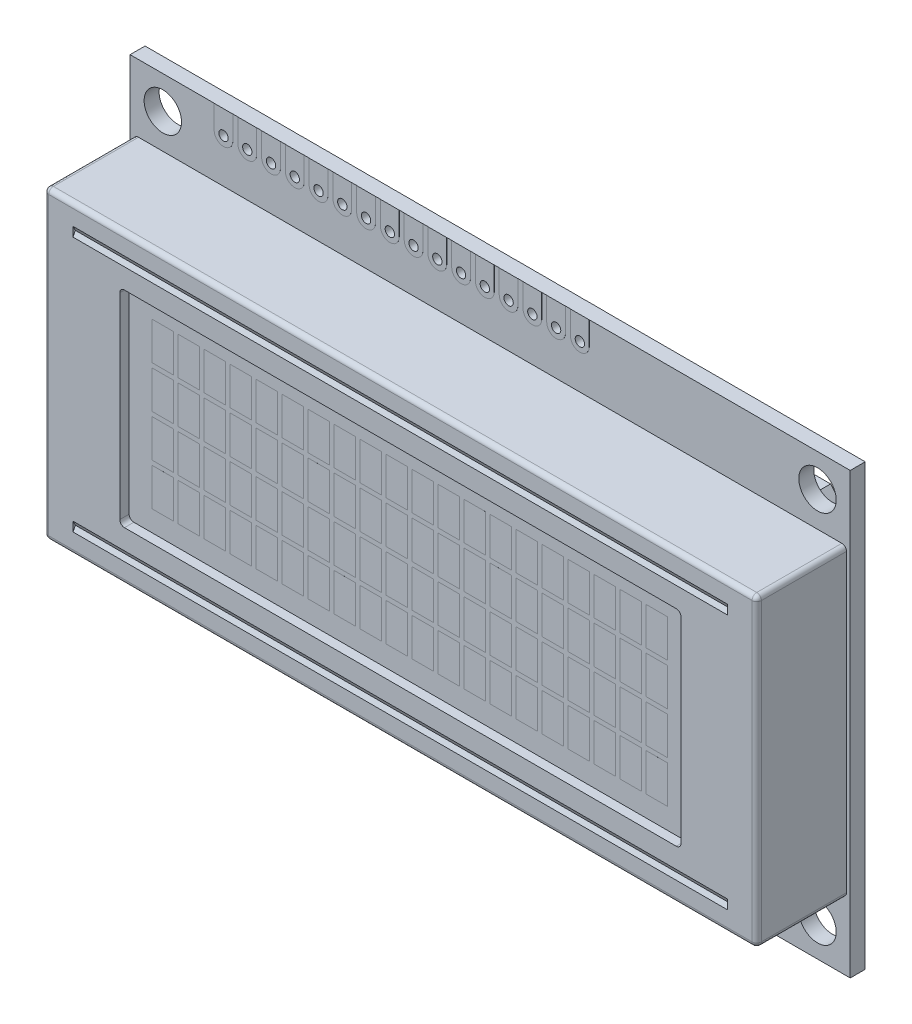
SolidWorks part; units mm, degrees
ref_plane "Plan de face" through (0, 0, 0) normal (0, 0, 1) x (1, 0, 0)
ref_plane "Plan de dessus" through (0, 0, 0) normal (0, 1, 0) x (1, 0, 0)
ref_plane "Plan de droite" through (0, 0, 0) normal (1, 0, 0) x (0, 0, -1)
sketch "Esquisse1" plane through (0, 0, 0) normal (0, 0, 1) x (1, 0, 0)
  line L0 (0, 23.5) -> (0, -23.5) construction
  line L1 (-38.5, 23.5) -> (38.5, 23.5)
  line L2 (-38.5, 23.5) -> (-38.5, -23.5)
  line L3 (-38.5, -23.5) -> (38.5, -23.5)
  line L4 (38.5, 23.5) -> (38.5, -23.5)
  line L5 (-38.5, 23.5) -> (38.5, -23.5) construction
  line L6 (-38.5, -23.5) -> (38.5, 23.5) construction
  line L7 (-38.5, 0) -> (38.5, 0) construction
  line L8 (-28.5, 21) -> (-25.96, 21) construction
  circle A0 centre (-35, 20) radius 2
  circle A1 centre (35, 20) radius 2
  circle A2 centre (-35, -20) radius 2
  circle A3 centre (35, -20) radius 2
  circle A4 centre (-28.5, 21) radius 0.5
  circle A5 centre (-25.96, 21) radius 0.5
  circle A6 centre (-23.42, 21) radius 0.5
  circle A7 centre (-20.88, 21) radius 0.5
  circle A8 centre (-18.34, 21) radius 0.5
  circle A9 centre (-15.8, 21) radius 0.5
  circle A10 centre (-13.26, 21) radius 0.5
  circle A11 centre (-10.72, 21) radius 0.5
  circle A12 centre (-8.18, 21) radius 0.5
  circle A13 centre (-5.64, 21) radius 0.5
  circle A14 centre (-3.1, 21) radius 0.5
  circle A15 centre (-0.56, 21) radius 0.5
  circle A16 centre (1.98, 21) radius 0.5
  circle A17 centre (4.52, 21) radius 0.5
  circle A18 centre (7.06, 21) radius 0.5
  circle A19 centre (9.6, 21) radius 0.5
  point P0 (0, 0)
  dimension "D3" = 4
  dimension "D6" = 10
  dimension "D7" = 1
  dimension "D1" = 77
  dimension "D2" = 47
  dimension "D4" = 40
  dimension "D5" = 70
  dimension "D8" = 2.5
  dimension "D10" = 2.54
  dimension "D9" = 16
extrude "PCB" add sketch "Esquisse1" along normal blind 1.6
ref_plane "Plan mi-PCB" through (0, 0, 0.8) normal (0, 0, 1) x (1, 0, 0)
sketch "Esquisse6" plane through (0, 0, 1.6) normal (0, 0, 1) x (1, 0, 0)
  line L0 (-29.5, 21) -> (-29.5, 23.5)
  line L1 (38.5, 23.5) -> (-38.5, 23.5) construction
  line L2 (-29.5, 23.5) -> (-27.5, 23.5)
  line L3 (-27.5, 23.5) -> (-27.5, 21)
  line L4 (-24.96, 23.5) -> (-24.96, 21)
  line L5 (-26.96, 21) -> (-26.96, 23.5)
  line L6 (-26.96, 23.5) -> (-24.96, 23.5)
  line L7 (-22.42, 23.5) -> (-22.42, 21)
  line L8 (-24.42, 21) -> (-24.42, 23.5)
  line L9 (-24.42, 23.5) -> (-22.42, 23.5)
  line L10 (-19.88, 23.5) -> (-19.88, 21)
  line L11 (-21.88, 21) -> (-21.88, 23.5)
  line L12 (-21.88, 23.5) -> (-19.88, 23.5)
  line L13 (-17.34, 23.5) -> (-17.34, 21)
  line L14 (-19.34, 21) -> (-19.34, 23.5)
  line L15 (-19.34, 23.5) -> (-17.34, 23.5)
  line L16 (-14.8, 23.5) -> (-14.8, 21)
  line L17 (-16.8, 21) -> (-16.8, 23.5)
  line L18 (-16.8, 23.5) -> (-14.8, 23.5)
  line L19 (-12.26, 23.5) -> (-12.26, 21)
  line L20 (-14.26, 21) -> (-14.26, 23.5)
  line L21 (-14.26, 23.5) -> (-12.26, 23.5)
  line L22 (-9.72, 23.5) -> (-9.72, 21)
  line L23 (-11.72, 21) -> (-11.72, 23.5)
  line L24 (-11.72, 23.5) -> (-9.72, 23.5)
  line L25 (-7.18, 23.5) -> (-7.18, 21)
  line L26 (-9.18, 21) -> (-9.18, 23.5)
  line L27 (-9.18, 23.5) -> (-7.18, 23.5)
  line L28 (-4.64, 23.5) -> (-4.64, 21)
  line L29 (-6.64, 21) -> (-6.64, 23.5)
  line L30 (-6.64, 23.5) -> (-4.64, 23.5)
  line L31 (-2.1, 23.5) -> (-2.1, 21)
  line L32 (-4.1, 21) -> (-4.1, 23.5)
  line L33 (-4.1, 23.5) -> (-2.1, 23.5)
  line L34 (0.44, 23.5) -> (0.44, 21)
  line L35 (-1.56, 21) -> (-1.56, 23.5)
  line L36 (-1.56, 23.5) -> (0.44, 23.5)
  line L37 (2.98, 23.5) -> (2.98, 21)
  line L38 (0.98, 21) -> (0.98, 23.5)
  line L39 (0.98, 23.5) -> (2.98, 23.5)
  line L40 (5.52, 23.5) -> (5.52, 21)
  line L41 (3.52, 21) -> (3.52, 23.5)
  line L42 (3.52, 23.5) -> (5.52, 23.5)
  line L43 (8.06, 23.5) -> (8.06, 21)
  line L44 (6.06, 21) -> (6.06, 23.5)
  line L45 (6.06, 23.5) -> (8.06, 23.5)
  line L46 (10.6, 23.5) -> (10.6, 21)
  line L47 (8.6, 21) -> (8.6, 23.5)
  line L48 (8.6, 23.5) -> (10.6, 23.5)
  line L49 (-27.5, 23.5) -> (-24.96, 23.5) construction
  arc A0 (-29.5, 21) -> (-27.5, 21) centre (-28.5, 21) ccw
  circle A1 centre (-28.5, 21) radius 0.5 construction
  circle A2 centre (-28.5, 21) radius 0.5
  arc A3 (-26.96, 21) -> (-24.96, 21) centre (-25.96, 21) ccw
  circle A4 centre (-25.96, 21) radius 0.5
  arc A5 (-24.42, 21) -> (-22.42, 21) centre (-23.42, 21) ccw
  circle A6 centre (-23.42, 21) radius 0.5
  arc A7 (-21.88, 21) -> (-19.88, 21) centre (-20.88, 21) ccw
  circle A8 centre (-20.88, 21) radius 0.5
  arc A9 (-19.34, 21) -> (-17.34, 21) centre (-18.34, 21) ccw
  circle A10 centre (-18.34, 21) radius 0.5
  arc A11 (-16.8, 21) -> (-14.8, 21) centre (-15.8, 21) ccw
  circle A12 centre (-15.8, 21) radius 0.5
  arc A13 (-14.26, 21) -> (-12.26, 21) centre (-13.26, 21) ccw
  circle A14 centre (-13.26, 21) radius 0.5
  arc A15 (-11.72, 21) -> (-9.72, 21) centre (-10.72, 21) ccw
  circle A16 centre (-10.72, 21) radius 0.5
  arc A17 (-9.18, 21) -> (-7.18, 21) centre (-8.18, 21) ccw
  circle A18 centre (-8.18, 21) radius 0.5
  arc A19 (-6.64, 21) -> (-4.64, 21) centre (-5.64, 21) ccw
  circle A20 centre (-5.64, 21) radius 0.5
  arc A21 (-4.1, 21) -> (-2.1, 21) centre (-3.1, 21) ccw
  circle A22 centre (-3.1, 21) radius 0.5
  arc A23 (-1.56, 21) -> (0.44, 21) centre (-0.56, 21) ccw
  circle A24 centre (-0.56, 21) radius 0.5
  arc A25 (0.98, 21) -> (2.98, 21) centre (1.98, 21) ccw
  circle A26 centre (1.98, 21) radius 0.5
  arc A27 (3.52, 21) -> (5.52, 21) centre (4.52, 21) ccw
  circle A28 centre (4.52, 21) radius 0.5
  arc A29 (6.06, 21) -> (8.06, 21) centre (7.06, 21) ccw
  circle A30 centre (7.06, 21) radius 0.5
  arc A31 (8.6, 21) -> (10.6, 21) centre (9.6, 21) ccw
  circle A32 centre (9.6, 21) radius 0.5
  dimension "D1" = 2
  dimension "D3" = 2.54
  dimension "D2" = 16
extrude "Pads" add sketch "Esquisse6" along normal blind 0.01
mirror "Symétrie1" about plane through (0, 0, 0.8) normal (0, 0, 1) of "Pads"
sketch "Esquisse2" plane through (0, 0, 1.6) normal (0, 0, 1) x (1, 0, 0)
  line L0 (38.5, 23.5) -> (10.6, 23.5) construction
  line L1 (-38.1, 16.3) -> (38.1, 16.3)
  line L2 (-38.1, 16.3) -> (-38.1, -16.3)
  line L3 (-38.1, -16.3) -> (38.1, -16.3)
  line L4 (38.1, 16.3) -> (38.1, -16.3)
  line L5 (-38.1, 16.3) -> (38.1, -16.3) construction
  line L6 (-38.1, -16.3) -> (38.1, 16.3) construction
  line L7 (38.5, -23.5) -> (38.5, 23.5) construction
  point P0 (0, 0)
  dimension "D1" = 76.2
  dimension "D2" = 32.6
  dimension "D3" = 7.2
  dimension "D4" = 0.4
extrude "capot ecran" add sketch "Esquisse2" along normal blind 9.6
fillet "Congé capot" radius 0.5 8 edges at (0, -16.3, 11.2) (-38.1, 0, 11.2) (0, 16.3, 11.2) (38.1, 0, 11.2) (-38.1, -16.3, 6.4) (-38.1, 16.3, 6.4) (38.1, -16.3, 6.4) (38.1, 16.3, 6.4)
sketch "Esquisse3" plane through (0, 0, 11.2) normal (0, 0, 1) x (1, 0, 0)
  line L1 (-29.5, 11) -> (29.5, 11)
  line L2 (-30, 10.5) -> (-30, -10.5)
  line L3 (-29.5, -11) -> (29.5, -11)
  line L4 (30, 10.5) -> (30, -10.5)
  line L5 (-30, 11) -> (30, -11) construction
  line L6 (-30, -11) -> (30, 11) construction
  line L7 (38.5, -23.5) -> (38.5, 23.5) construction
  line L8 (38.5, 23.5) -> (10.6, 23.5) construction
  arc A0 (30, -10.5) -> (29.5, -11) centre (29.5, -10.5) cw
  arc A1 (-29.5, -11) -> (-30, -10.5) centre (-29.5, -10.5) cw
  arc A2 (-30, 10.5) -> (-29.5, 11) centre (-29.5, 10.5) cw
  arc A3 (29.5, 11) -> (30, 10.5) centre (29.5, 10.5) cw
  point P0 (0, 0)
  dimension "D3" = 0.5
  dimension "D1" = 60
  dimension "D2" = 22
  dimension "D4" = 8.5
  dimension "D5" = 12.5
extrude "ecran" cut sketch "Esquisse3" against normal blind 1
sketch "Esquisse4" plane through (0, 0, 10.2) normal (0, 0, 1) x (1, 0, 0)
  line L0 (-24.78, 4.75) -> (-22.48, 4.75)
  line L1 (-27.56, 8.78) -> (-25.26, 8.78)
  line L2 (-27.56, 8.78) -> (-27.56, 4.75)
  line L3 (-27.56, 4.75) -> (-25.26, 4.75)
  line L4 (-25.26, 8.78) -> (-25.26, 4.75)
  line L5 (-22.48, 8.78) -> (-22.48, 4.75)
  line L6 (-24.78, 8.78) -> (-22.48, 8.78)
  line L7 (-24.78, 8.78) -> (-24.78, 4.75)
  line L8 (-22, 4.75) -> (-19.7, 4.75)
  line L9 (-19.7, 8.78) -> (-19.7, 4.75)
  line L10 (-22, 8.78) -> (-19.7, 8.78)
  line L11 (-22, 8.78) -> (-22, 4.75)
  line L12 (-19.22, 4.75) -> (-16.92, 4.75)
  line L13 (-16.92, 8.78) -> (-16.92, 4.75)
  line L14 (-19.22, 8.78) -> (-16.92, 8.78)
  line L15 (-19.22, 8.78) -> (-19.22, 4.75)
  line L16 (-16.44, 4.75) -> (-14.14, 4.75)
  line L17 (-14.14, 8.78) -> (-14.14, 4.75)
  line L18 (-16.44, 8.78) -> (-14.14, 8.78)
  line L19 (-16.44, 8.78) -> (-16.44, 4.75)
  line L20 (-13.66, 4.75) -> (-11.36, 4.75)
  line L21 (-11.36, 8.78) -> (-11.36, 4.75)
  line L22 (-13.66, 8.78) -> (-11.36, 8.78)
  line L23 (-13.66, 8.78) -> (-13.66, 4.75)
  line L24 (-10.88, 4.75) -> (-8.58, 4.75)
  line L25 (-8.58, 8.78) -> (-8.58, 4.75)
  line L26 (-10.88, 8.78) -> (-8.58, 8.78)
  line L27 (-10.88, 8.78) -> (-10.88, 4.75)
  line L28 (-8.1, 4.75) -> (-5.8, 4.75)
  line L29 (-5.8, 8.78) -> (-5.8, 4.75)
  line L30 (-8.1, 8.78) -> (-5.8, 8.78)
  line L31 (-8.1, 8.78) -> (-8.1, 4.75)
  line L32 (-5.32, 4.75) -> (-3.02, 4.75)
  line L33 (-3.02, 8.78) -> (-3.02, 4.75)
  line L34 (-5.32, 8.78) -> (-3.02, 8.78)
  line L35 (-5.32, 8.78) -> (-5.32, 4.75)
  line L36 (-2.54, 4.75) -> (-0.24, 4.75)
  line L37 (-0.24, 8.78) -> (-0.24, 4.75)
  line L38 (-2.54, 8.78) -> (-0.24, 8.78)
  line L39 (-2.54, 8.78) -> (-2.54, 4.75)
  line L40 (0.24, 4.75) -> (2.54, 4.75)
  line L41 (2.54, 8.78) -> (2.54, 4.75)
  line L42 (0.24, 8.78) -> (2.54, 8.78)
  line L43 (0.24, 8.78) -> (0.24, 4.75)
  line L44 (3.02, 4.75) -> (5.32, 4.75)
  line L45 (5.32, 8.78) -> (5.32, 4.75)
  line L46 (3.02, 8.78) -> (5.32, 8.78)
  line L47 (3.02, 8.78) -> (3.02, 4.75)
  line L48 (5.8, 4.75) -> (8.1, 4.75)
  line L49 (8.1, 8.78) -> (8.1, 4.75)
  line L50 (5.8, 8.78) -> (8.1, 8.78)
  line L51 (5.8, 8.78) -> (5.8, 4.75)
  line L52 (8.58, 4.75) -> (10.88, 4.75)
  line L53 (10.88, 8.78) -> (10.88, 4.75)
  line L54 (8.58, 8.78) -> (10.88, 8.78)
  line L55 (8.58, 8.78) -> (8.58, 4.75)
  line L56 (11.36, 4.75) -> (13.66, 4.75)
  line L57 (13.66, 8.78) -> (13.66, 4.75)
  line L58 (11.36, 8.78) -> (13.66, 8.78)
  line L59 (11.36, 8.78) -> (11.36, 4.75)
  line L60 (14.14, 4.75) -> (16.44, 4.75)
  line L61 (16.44, 8.78) -> (16.44, 4.75)
  line L62 (14.14, 8.78) -> (16.44, 8.78)
  line L63 (14.14, 8.78) -> (14.14, 4.75)
  line L64 (16.92, 4.75) -> (19.22, 4.75)
  line L65 (19.22, 8.78) -> (19.22, 4.75)
  line L66 (16.92, 8.78) -> (19.22, 8.78)
  line L67 (16.92, 8.78) -> (16.92, 4.75)
  line L68 (19.7, 4.75) -> (22, 4.75)
  line L69 (22, 8.78) -> (22, 4.75)
  line L70 (19.7, 8.78) -> (22, 8.78)
  line L71 (19.7, 8.78) -> (19.7, 4.75)
  line L72 (22.48, 4.75) -> (24.78, 4.75)
  line L73 (24.78, 8.78) -> (24.78, 4.75)
  line L74 (22.48, 8.78) -> (24.78, 8.78)
  line L75 (22.48, 8.78) -> (22.48, 4.75)
  line L76 (25.26, 4.75) -> (27.56, 4.75)
  line L77 (27.56, 8.78) -> (27.56, 4.75)
  line L78 (25.26, 8.78) -> (27.56, 8.78)
  line L79 (25.26, 8.78) -> (25.26, 4.75)
  line L80 (-24.78, 0.24) -> (-22.48, 0.24)
  line L81 (-22.48, 4.27) -> (-22.48, 0.24)
  line L82 (-24.78, 4.27) -> (-22.48, 4.27)
  line L83 (-24.78, 4.27) -> (-24.78, 0.24)
  line L84 (-22, 0.24) -> (-19.7, 0.24)
  line L85 (-19.7, 4.27) -> (-19.7, 0.24)
  line L86 (-22, 4.27) -> (-19.7, 4.27)
  line L87 (-22, 4.27) -> (-22, 0.24)
  line L88 (-19.22, 0.24) -> (-16.92, 0.24)
  line L89 (-16.92, 4.27) -> (-16.92, 0.24)
  line L90 (-19.22, 4.27) -> (-16.92, 4.27)
  line L91 (-19.22, 4.27) -> (-19.22, 0.24)
  line L92 (-16.44, 0.24) -> (-14.14, 0.24)
  line L93 (-14.14, 4.27) -> (-14.14, 0.24)
  line L94 (-16.44, 4.27) -> (-14.14, 4.27)
  line L95 (-16.44, 4.27) -> (-16.44, 0.24)
  line L96 (-13.66, 0.24) -> (-11.36, 0.24)
  line L97 (-11.36, 4.27) -> (-11.36, 0.24)
  line L98 (-13.66, 4.27) -> (-11.36, 4.27)
  line L99 (-13.66, 4.27) -> (-13.66, 0.24)
  line L100 (-10.88, 0.24) -> (-8.58, 0.24)
  line L101 (-8.58, 4.27) -> (-8.58, 0.24)
  line L102 (-10.88, 4.27) -> (-8.58, 4.27)
  line L103 (-10.88, 4.27) -> (-10.88, 0.24)
  line L104 (-8.1, 0.24) -> (-5.8, 0.24)
  line L105 (-5.8, 4.27) -> (-5.8, 0.24)
  line L106 (-8.1, 4.27) -> (-5.8, 4.27)
  line L107 (-8.1, 4.27) -> (-8.1, 0.24)
  line L108 (-5.32, 0.24) -> (-3.02, 0.24)
  line L109 (-3.02, 4.27) -> (-3.02, 0.24)
  line L110 (-5.32, 4.27) -> (-3.02, 4.27)
  line L111 (-5.32, 4.27) -> (-5.32, 0.24)
  line L112 (-2.54, 0.24) -> (-0.24, 0.24)
  line L113 (-0.24, 4.27) -> (-0.24, 0.24)
  line L114 (-2.54, 4.27) -> (-0.24, 4.27)
  line L115 (-2.54, 4.27) -> (-2.54, 0.24)
  line L116 (0.24, 0.24) -> (2.54, 0.24)
  line L117 (2.54, 4.27) -> (2.54, 0.24)
  line L118 (0.24, 4.27) -> (2.54, 4.27)
  line L119 (0.24, 4.27) -> (0.24, 0.24)
  line L120 (3.02, 0.24) -> (5.32, 0.24)
  line L121 (5.32, 4.27) -> (5.32, 0.24)
  line L122 (3.02, 4.27) -> (5.32, 4.27)
  line L123 (3.02, 4.27) -> (3.02, 0.24)
  line L124 (5.8, 0.24) -> (8.1, 0.24)
  line L125 (8.1, 4.27) -> (8.1, 0.24)
  line L126 (5.8, 4.27) -> (8.1, 4.27)
  line L127 (5.8, 4.27) -> (5.8, 0.24)
  line L128 (8.58, 0.24) -> (10.88, 0.24)
  line L129 (10.88, 4.27) -> (10.88, 0.24)
  line L130 (8.58, 4.27) -> (10.88, 4.27)
  line L131 (8.58, 4.27) -> (8.58, 0.24)
  line L132 (11.36, 0.24) -> (13.66, 0.24)
  line L133 (13.66, 4.27) -> (13.66, 0.24)
  line L134 (11.36, 4.27) -> (13.66, 4.27)
  line L135 (11.36, 4.27) -> (11.36, 0.24)
  line L136 (14.14, 0.24) -> (16.44, 0.24)
  line L137 (16.44, 4.27) -> (16.44, 0.24)
  line L138 (14.14, 4.27) -> (16.44, 4.27)
  line L139 (14.14, 4.27) -> (14.14, 0.24)
  line L140 (16.92, 0.24) -> (19.22, 0.24)
  line L141 (19.22, 4.27) -> (19.22, 0.24)
  line L142 (16.92, 4.27) -> (19.22, 4.27)
  line L143 (16.92, 4.27) -> (16.92, 0.24)
  line L144 (19.7, 0.24) -> (22, 0.24)
  line L145 (22, 4.27) -> (22, 0.24)
  line L146 (19.7, 4.27) -> (22, 4.27)
  line L147 (19.7, 4.27) -> (19.7, 0.24)
  line L148 (22.48, 0.24) -> (24.78, 0.24)
  line L149 (24.78, 4.27) -> (24.78, 0.24)
  line L150 (22.48, 4.27) -> (24.78, 4.27)
  line L151 (22.48, 4.27) -> (22.48, 0.24)
  line L152 (25.26, 0.24) -> (27.56, 0.24)
  line L153 (27.56, 4.27) -> (27.56, 0.24)
  line L154 (25.26, 4.27) -> (27.56, 4.27)
  line L155 (25.26, 4.27) -> (25.26, 0.24)
  line L156 (-24.78, -4.27) -> (-22.48, -4.27)
  line L157 (-22.48, -0.24) -> (-22.48, -4.27)
  line L158 (-24.78, -0.24) -> (-22.48, -0.24)
  line L159 (-24.78, -0.24) -> (-24.78, -4.27)
  line L160 (-22, -4.27) -> (-19.7, -4.27)
  line L161 (-19.7, -0.24) -> (-19.7, -4.27)
  line L162 (-22, -0.24) -> (-19.7, -0.24)
  line L163 (-22, -0.24) -> (-22, -4.27)
  line L164 (-19.22, -4.27) -> (-16.92, -4.27)
  line L165 (-16.92, -0.24) -> (-16.92, -4.27)
  line L166 (-19.22, -0.24) -> (-16.92, -0.24)
  line L167 (-19.22, -0.24) -> (-19.22, -4.27)
  line L168 (-16.44, -4.27) -> (-14.14, -4.27)
  line L169 (-14.14, -0.24) -> (-14.14, -4.27)
  line L170 (-16.44, -0.24) -> (-14.14, -0.24)
  line L171 (-16.44, -0.24) -> (-16.44, -4.27)
  line L172 (-13.66, -4.27) -> (-11.36, -4.27)
  line L173 (-11.36, -0.24) -> (-11.36, -4.27)
  line L174 (-13.66, -0.24) -> (-11.36, -0.24)
  line L175 (-13.66, -0.24) -> (-13.66, -4.27)
  line L176 (-10.88, -4.27) -> (-8.58, -4.27)
  line L177 (-8.58, -0.24) -> (-8.58, -4.27)
  line L178 (-10.88, -0.24) -> (-8.58, -0.24)
  line L179 (-10.88, -0.24) -> (-10.88, -4.27)
  line L180 (-8.1, -4.27) -> (-5.8, -4.27)
  line L181 (-5.8, -0.24) -> (-5.8, -4.27)
  line L182 (-8.1, -0.24) -> (-5.8, -0.24)
  line L183 (-8.1, -0.24) -> (-8.1, -4.27)
  line L184 (-5.32, -4.27) -> (-3.02, -4.27)
  line L185 (-3.02, -0.24) -> (-3.02, -4.27)
  line L186 (-5.32, -0.24) -> (-3.02, -0.24)
  line L187 (-5.32, -0.24) -> (-5.32, -4.27)
  line L188 (-2.54, -4.27) -> (-0.24, -4.27)
  line L189 (-0.24, -0.24) -> (-0.24, -4.27)
  line L190 (-2.54, -0.24) -> (-0.24, -0.24)
  line L191 (-2.54, -0.24) -> (-2.54, -4.27)
  line L192 (0.24, -4.27) -> (2.54, -4.27)
  line L193 (2.54, -0.24) -> (2.54, -4.27)
  line L194 (0.24, -0.24) -> (2.54, -0.24)
  line L195 (0.24, -0.24) -> (0.24, -4.27)
  line L196 (3.02, -4.27) -> (5.32, -4.27)
  line L197 (5.32, -0.24) -> (5.32, -4.27)
  line L198 (3.02, -0.24) -> (5.32, -0.24)
  line L199 (3.02, -0.24) -> (3.02, -4.27)
  line L200 (5.8, -4.27) -> (8.1, -4.27)
  line L201 (8.1, -0.24) -> (8.1, -4.27)
  line L202 (5.8, -0.24) -> (8.1, -0.24)
  line L203 (5.8, -0.24) -> (5.8, -4.27)
  line L204 (8.58, -4.27) -> (10.88, -4.27)
  line L205 (10.88, -0.24) -> (10.88, -4.27)
  line L206 (8.58, -0.24) -> (10.88, -0.24)
  line L207 (8.58, -0.24) -> (8.58, -4.27)
  line L208 (11.36, -4.27) -> (13.66, -4.27)
  line L209 (13.66, -0.24) -> (13.66, -4.27)
  line L210 (11.36, -0.24) -> (13.66, -0.24)
  line L211 (11.36, -0.24) -> (11.36, -4.27)
  line L212 (14.14, -4.27) -> (16.44, -4.27)
  line L213 (16.44, -0.24) -> (16.44, -4.27)
  line L214 (14.14, -0.24) -> (16.44, -0.24)
  line L215 (14.14, -0.24) -> (14.14, -4.27)
  line L216 (16.92, -4.27) -> (19.22, -4.27)
  line L217 (19.22, -0.24) -> (19.22, -4.27)
  line L218 (16.92, -0.24) -> (19.22, -0.24)
  line L219 (16.92, -0.24) -> (16.92, -4.27)
  line L220 (19.7, -4.27) -> (22, -4.27)
  line L221 (22, -0.24) -> (22, -4.27)
  line L222 (19.7, -0.24) -> (22, -0.24)
  line L223 (19.7, -0.24) -> (19.7, -4.27)
  line L224 (22.48, -4.27) -> (24.78, -4.27)
  line L225 (24.78, -0.24) -> (24.78, -4.27)
  line L226 (22.48, -0.24) -> (24.78, -0.24)
  line L227 (22.48, -0.24) -> (22.48, -4.27)
  line L228 (25.26, -4.27) -> (27.56, -4.27)
  line L229 (27.56, -0.24) -> (27.56, -4.27)
  line L230 (25.26, -0.24) -> (27.56, -0.24)
  line L231 (25.26, -0.24) -> (25.26, -4.27)
  line L232 (-24.78, -8.78) -> (-22.48, -8.78)
  line L233 (-22.48, -4.75) -> (-22.48, -8.78)
  line L234 (-24.78, -4.75) -> (-22.48, -4.75)
  line L235 (-24.78, -4.75) -> (-24.78, -8.78)
  line L236 (-22, -8.78) -> (-19.7, -8.78)
  line L237 (-19.7, -4.75) -> (-19.7, -8.78)
  line L238 (-22, -4.75) -> (-19.7, -4.75)
  line L239 (-22, -4.75) -> (-22, -8.78)
  line L240 (-19.22, -8.78) -> (-16.92, -8.78)
  line L241 (-16.92, -4.75) -> (-16.92, -8.78)
  line L242 (-19.22, -4.75) -> (-16.92, -4.75)
  line L243 (-19.22, -4.75) -> (-19.22, -8.78)
  line L244 (-16.44, -8.78) -> (-14.14, -8.78)
  line L245 (-14.14, -4.75) -> (-14.14, -8.78)
  line L246 (-16.44, -4.75) -> (-14.14, -4.75)
  line L247 (-16.44, -4.75) -> (-16.44, -8.78)
  line L248 (-13.66, -8.78) -> (-11.36, -8.78)
  line L249 (-11.36, -4.75) -> (-11.36, -8.78)
  line L250 (-13.66, -4.75) -> (-11.36, -4.75)
  line L251 (-13.66, -4.75) -> (-13.66, -8.78)
  line L252 (-10.88, -8.78) -> (-8.58, -8.78)
  line L253 (-8.58, -4.75) -> (-8.58, -8.78)
  line L254 (-10.88, -4.75) -> (-8.58, -4.75)
  line L255 (-10.88, -4.75) -> (-10.88, -8.78)
  line L256 (-8.1, -8.78) -> (-5.8, -8.78)
  line L257 (-5.8, -4.75) -> (-5.8, -8.78)
  line L258 (-8.1, -4.75) -> (-5.8, -4.75)
  line L259 (-8.1, -4.75) -> (-8.1, -8.78)
  line L260 (-5.32, -8.78) -> (-3.02, -8.78)
  line L261 (-3.02, -4.75) -> (-3.02, -8.78)
  line L262 (-5.32, -4.75) -> (-3.02, -4.75)
  line L263 (-5.32, -4.75) -> (-5.32, -8.78)
  line L264 (-2.54, -8.78) -> (-0.24, -8.78)
  line L265 (-0.24, -4.75) -> (-0.24, -8.78)
  line L266 (-2.54, -4.75) -> (-0.24, -4.75)
  line L267 (-2.54, -4.75) -> (-2.54, -8.78)
  line L268 (0.24, -8.78) -> (2.54, -8.78)
  line L269 (2.54, -4.75) -> (2.54, -8.78)
  line L270 (0.24, -4.75) -> (2.54, -4.75)
  line L271 (0.24, -4.75) -> (0.24, -8.78)
  line L272 (3.02, -8.78) -> (5.32, -8.78)
  line L273 (5.32, -4.75) -> (5.32, -8.78)
  line L274 (3.02, -4.75) -> (5.32, -4.75)
  line L275 (3.02, -4.75) -> (3.02, -8.78)
  line L276 (5.8, -8.78) -> (8.1, -8.78)
  line L277 (8.1, -4.75) -> (8.1, -8.78)
  line L278 (5.8, -4.75) -> (8.1, -4.75)
  line L279 (5.8, -4.75) -> (5.8, -8.78)
  line L280 (8.58, -8.78) -> (10.88, -8.78)
  line L281 (10.88, -4.75) -> (10.88, -8.78)
  line L282 (8.58, -4.75) -> (10.88, -4.75)
  line L283 (8.58, -4.75) -> (8.58, -8.78)
  line L284 (11.36, -8.78) -> (13.66, -8.78)
  line L285 (13.66, -4.75) -> (13.66, -8.78)
  line L286 (11.36, -4.75) -> (13.66, -4.75)
  line L287 (11.36, -4.75) -> (11.36, -8.78)
  line L288 (14.14, -8.78) -> (16.44, -8.78)
  line L289 (16.44, -4.75) -> (16.44, -8.78)
  line L290 (14.14, -4.75) -> (16.44, -4.75)
  line L291 (14.14, -4.75) -> (14.14, -8.78)
  line L292 (16.92, -8.78) -> (19.22, -8.78)
  line L293 (19.22, -4.75) -> (19.22, -8.78)
  line L294 (16.92, -4.75) -> (19.22, -4.75)
  line L295 (16.92, -4.75) -> (16.92, -8.78)
  line L296 (19.7, -8.78) -> (22, -8.78)
  line L297 (22, -4.75) -> (22, -8.78)
  line L298 (19.7, -4.75) -> (22, -4.75)
  line L299 (19.7, -4.75) -> (19.7, -8.78)
  line L300 (22.48, -8.78) -> (24.78, -8.78)
  line L301 (24.78, -4.75) -> (24.78, -8.78)
  line L302 (22.48, -4.75) -> (24.78, -4.75)
  line L303 (22.48, -4.75) -> (22.48, -8.78)
  line L304 (25.26, -8.78) -> (27.56, -8.78)
  line L305 (27.56, -4.75) -> (27.56, -8.78)
  line L306 (25.26, -4.75) -> (27.56, -4.75)
  line L307 (25.26, -4.75) -> (25.26, -8.78)
  line L308 (-27.56, 0.24) -> (-25.26, 0.24)
  line L309 (-25.26, 4.27) -> (-25.26, 0.24)
  line L310 (-27.56, 4.27) -> (-25.26, 4.27)
  line L311 (-27.56, 4.27) -> (-27.56, 0.24)
  line L312 (-27.56, -4.27) -> (-25.26, -4.27)
  line L313 (-25.26, -0.24) -> (-25.26, -4.27)
  line L314 (-27.56, -0.24) -> (-25.26, -0.24)
  line L315 (-27.56, -0.24) -> (-27.56, -4.27)
  line L316 (-27.56, -8.78) -> (-25.26, -8.78)
  line L317 (-25.26, -4.75) -> (-25.26, -8.78)
  line L318 (-27.56, -4.75) -> (-25.26, -4.75)
  line L319 (-27.56, -4.75) -> (-27.56, -8.78)
  line L320 (-27.56, 4.75) -> (-24.78, 4.75) construction
  line L321 (-27.56, 4.75) -> (-27.56, 0.24) construction
  line L322 (0, 11) -> (0, -11) construction
  line L323 (29.5, 11) -> (-29.5, 11) construction
  line L324 (-29.5, -11) -> (29.5, -11) construction
  line L325 (-0.24, 8.78) -> (0.24, 8.78) construction
  line L326 (-27.56, 0.24) -> (-27.56, -0.24) construction
  line L327 (-30, 0) -> (30, 0) construction
  line L328 (-30, 10.5) -> (-30, -10.5) construction
  line L329 (30, -10.5) -> (30, 10.5) construction
  point P4 (0, 8.78)
  point P336 (-27.56, 0)
  dimension "D1" = 2.3
  dimension "D2" = 4.03
  dimension "D5" = 2.78
  dimension "D6" = 4.51
  dimension "D7" = 55.12
  dimension "D8" = 17.56
  dimension "D3" = 20
  dimension "D4" = 4
extrude "caracteres" add sketch "Esquisse4" along normal blind 0.0001
sketch "Esquisse5" plane through (0, 0, 0) normal (1, 0, 0) x (0, 0, -1)
  line L0 (-11.2, 0) -> (-3.384, 0) construction
  line L1 (-11.2, -15.8) -> (-11.2, 15.8) construction
  line L2 (-11.2, 14.15) -> (-11.2, 13.15)
  line L3 (-11.2, 13.15) -> (-10.95, 13.65)
  line L4 (-10.95, 13.65) -> (-11.2, 14.15)
  line L5 (-11.2, -14.15) -> (-11.2, -13.15)
  line L6 (-10.95, -13.65) -> (-11.2, -14.15)
  line L7 (-11.2, -13.15) -> (-10.95, -13.65)
  point P8 (-11.2, 13.65)
  dimension "D1" = 1
  dimension "D2" = 0.25
  dimension "D3" = 27.3
extrude "lignes capot" cut sketch "Esquisse5" against normal mid plane 70
sketch "Esquisse7" plane through (0, 0, 0) normal (0, 0, -1) x (-1, 0, 0)
  line L0 (0, 17.9709) -> (0, -18.837) construction
  line L1 (-32.635, 0) -> (33.2255, 0) construction
  line L2 (28.5, -16.3) -> (28.5, -15.8)
  line L3 (37.6, -16.3) -> (-37.6, -16.3) construction
  line L4 (28.5, -15.8) -> (31.2688, -15.8)
  line L5 (31.2688, -15.8) -> (32.1191, -14.8)
  line L6 (32.1191, -14.8) -> (32.5, -15.1239)
  line L7 (32.5, -15.1239) -> (31.5, -16.3)
  line L8 (31.5, -16.3) -> (28.5, -16.3)
  line L10 (38.5, 23.5) -> (38.5, -23.5) construction
  line L11 (11.5, -16.3) -> (8.5, -16.3)
  line L12 (8.5, -16.3) -> (8.5, -15.8)
  line L13 (8.5, -15.8) -> (11.2688, -15.8)
  line L14 (11.2688, -15.8) -> (12.1191, -14.8)
  line L15 (12.1191, -14.8) -> (12.5, -15.1239)
  line L16 (12.5, -15.1239) -> (11.5, -16.3)
  line L17 (31.5, -16.3) -> (11.5, -16.3) construction
  line L18 (-28.5, -16.3) -> (-28.5, -15.8)
  line L19 (-31.5, -16.3) -> (-28.5, -16.3)
  line L20 (-32.5, -15.1239) -> (-31.5, -16.3)
  line L21 (-32.1191, -14.8) -> (-32.5, -15.1239)
  line L22 (-31.2688, -15.8) -> (-32.1191, -14.8)
  line L23 (-28.5, -15.8) -> (-31.2688, -15.8)
  line L24 (-8.5, -16.3) -> (-8.5, -15.8)
  line L25 (-11.5, -16.3) -> (-8.5, -16.3)
  line L26 (-12.5, -15.1239) -> (-11.5, -16.3)
  line L27 (-12.1191, -14.8) -> (-12.5, -15.1239)
  line L28 (-11.2688, -15.8) -> (-12.1191, -14.8)
  line L29 (-8.5, -15.8) -> (-11.2688, -15.8)
  line L30 (-28.5, 15.8) -> (-31.2688, 15.8)
  line L31 (-28.5, 16.3) -> (-28.5, 15.8)
  line L32 (-31.5, 16.3) -> (-28.5, 16.3)
  line L33 (-32.5, 15.1239) -> (-31.5, 16.3)
  line L34 (-32.1191, 14.8) -> (-32.5, 15.1239)
  line L35 (-31.2688, 15.8) -> (-32.1191, 14.8)
  line L36 (-8.5, 15.8) -> (-11.2688, 15.8)
  line L37 (-8.5, 16.3) -> (-8.5, 15.8)
  line L38 (-11.5, 16.3) -> (-8.5, 16.3)
  line L39 (-12.5, 15.1239) -> (-11.5, 16.3)
  line L40 (-12.1191, 14.8) -> (-12.5, 15.1239)
  line L41 (-11.2688, 15.8) -> (-12.1191, 14.8)
  line L42 (28.5, 16.3) -> (28.5, 15.8)
  line L43 (31.5, 16.3) -> (28.5, 16.3)
  line L44 (32.5, 15.1239) -> (31.5, 16.3)
  line L45 (32.1191, 14.8) -> (32.5, 15.1239)
  line L46 (31.2688, 15.8) -> (32.1191, 14.8)
  line L47 (28.5, 15.8) -> (31.2688, 15.8)
  line L48 (8.5, 16.3) -> (8.5, 15.8)
  line L49 (11.5, 16.3) -> (8.5, 16.3)
  line L50 (12.5, 15.1239) -> (11.5, 16.3)
  line L51 (12.1191, 14.8) -> (12.5, 15.1239)
  line L52 (11.2688, 15.8) -> (12.1191, 14.8)
  line L53 (8.5, 15.8) -> (11.2688, 15.8)
  dimension "D1" = 4
  dimension "D2" = 3
  dimension "D3" = 0.5
  dimension "D4" = 1.5
  dimension "D5" = 10
  dimension "D7" = 20
  dimension "D6" = 2
extrude "languettes capot" add sketch "Esquisse7" along normal blind 3.3
